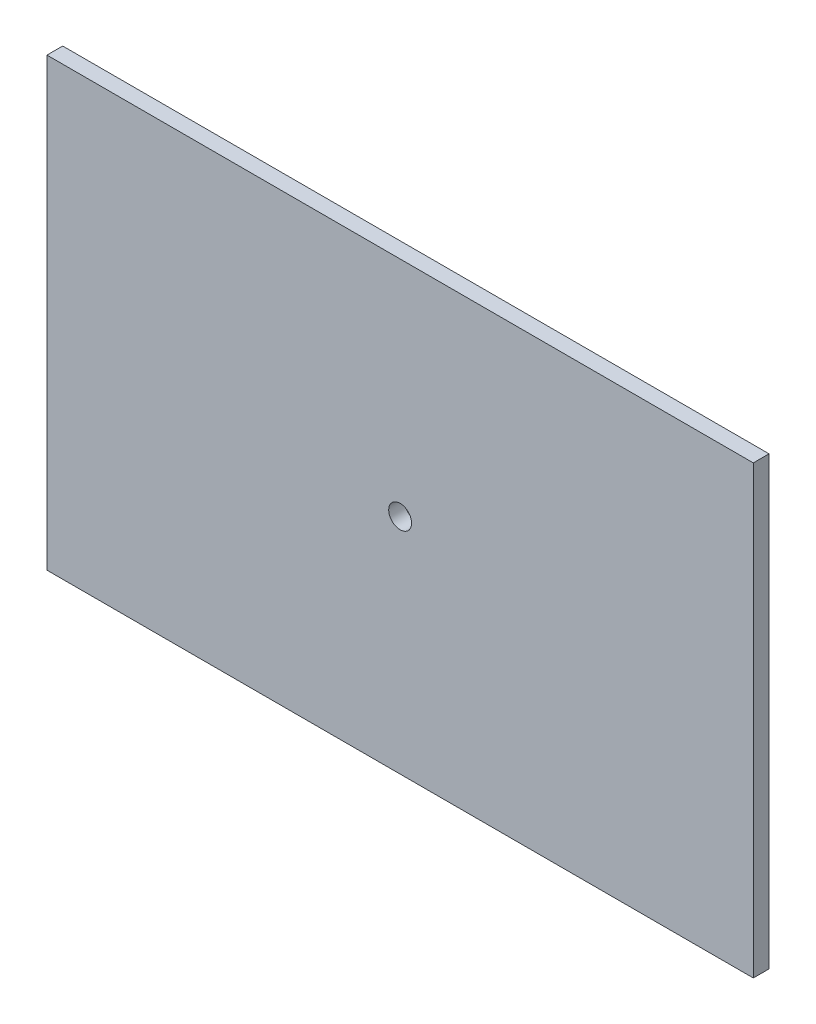
SolidWorks part; units mm, degrees
material "A-Glass Fiber"
ref_plane "Front Plane" through (0, 0, 0) normal (0, 0, 1) x (1, 0, 0)
ref_plane "Top Plane" through (0, 0, 0) normal (0, 1, 0) x (1, 0, 0)
ref_plane "Right Plane" through (0, 0, 0) normal (1, 0, 0) x (0, 0, -1)
sketch "Sketch1" plane through (0, 0, 0) normal (0, 0, 1) x (1, 0, 0)
  line L1 (0, 0) -> (784.225, 0)
  line L2 (0, 0) -> (0, 495.3)
  line L3 (0, 495.3) -> (784.225, 495.3)
  line L4 (784.225, 0) -> (784.225, 495.3)
  dimension "D1" = 495.3
  dimension "D2" = 784.225
extrude "Boss-Extrude1" add sketch "Sketch1" along normal blind 17.4625
sketch "Sketch2" plane through (0, 0, 17.4625) normal (0, 0, 1) x (1, 0, 0)
  circle A0 centre (392.1125, 247.65) radius 12.7
  dimension "D1" = 25.4
extrude "Cut-Extrude1" cut sketch "Sketch2" against normal blind 17.4625
